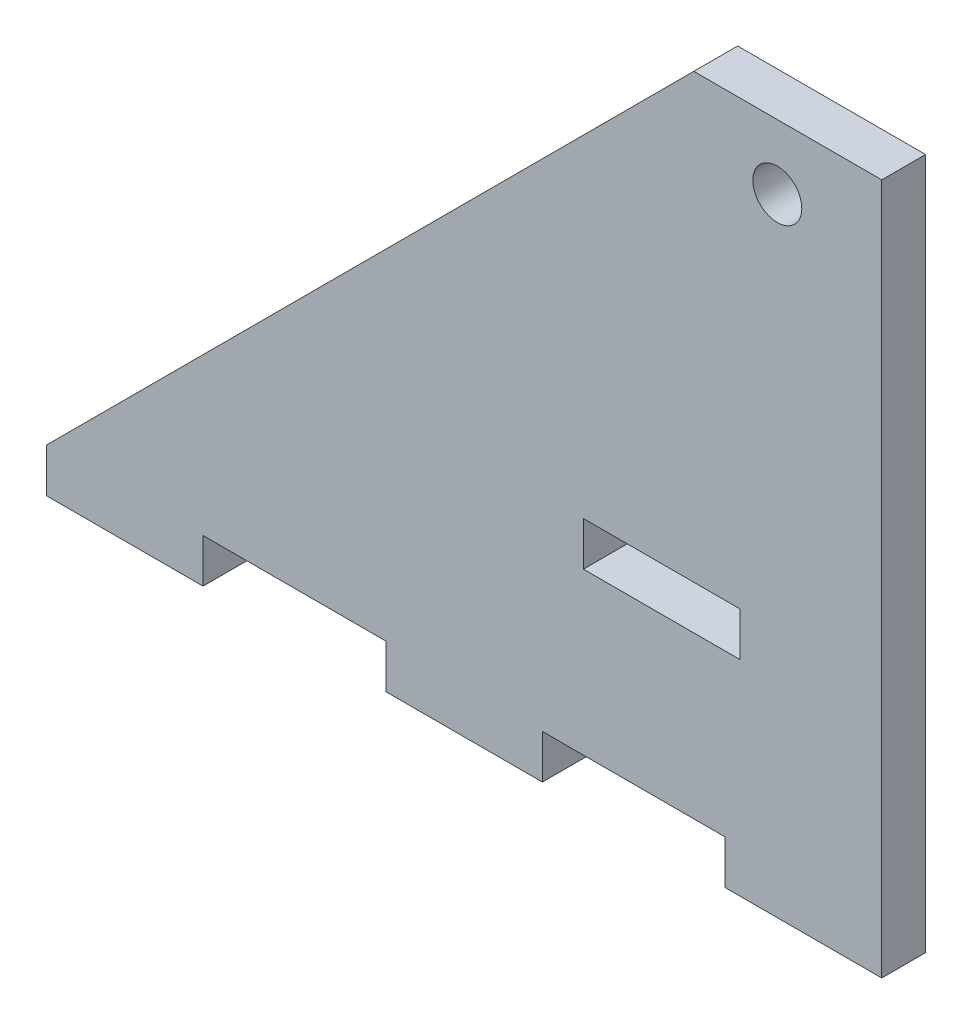
SolidWorks part; units mm, degrees
ref_plane "Front Plane" through (0, 0, 0) normal (0, 0, 1) x (1, 0, 0)
ref_plane "Top Plane" through (0, 0, 0) normal (0, 1, 0) x (1, 0, 0)
ref_plane "Right Plane" through (0, 0, 0) normal (1, 0, 0) x (0, 0, -1)
sketch "Sketch1" plane through (0, 0, 0) normal (0, 0, 1) x (1, 0, 0)
  line L0 (78.74, 78.74) -> (0, 0)
  line L1 (0, 0) -> (101.6, 0)
  line L3 (78.74, 78.74) -> (101.6, 78.74)
  line L4 (101.6, 0) -> (101.6, 78.74)
  dimension "D1" = 101.6
  dimension "D2" = 78.74
  dimension "D3" = 45
extrude "Base" add sketch "Sketch1" along normal blind 5.334
sketch "Sketch2" plane through (0, 0, 5.334) normal (0, 0, 1) x (1, 0, 0)
  line L0 (0, 0) -> (101.6, 0) construction
  line L1 (101.6, 0) -> (101.6, 78.74) construction
  line L2 (74.84, 46.5134) -> (74.84, 24.9234) construction
  line L3 (65.315, 24.9234) -> (84.365, 24.9234)
  line L4 (65.315, 24.9234) -> (65.315, 19.5894)
  line L5 (65.315, 19.5894) -> (84.365, 19.5894)
  line L6 (84.365, 24.9234) -> (84.365, 19.5894)
  line L7 (88.9, 70.866) -> (-24911.1, -43230.4042) construction
  circle A0 centre (88.9, 70.866) radius 2.975
  circle A1 centre (74.84, 46.5134) radius 3 construction
  dimension "D1" = 5.95
  dimension "D4" = 6
  dimension "D2" = 70.866
  dimension "D3" = 12.7
  dimension "D5" = 28.12
  dimension "D6" = 19.05
  dimension "D7" = 5.334
  dimension "D8" = 21.59
  dimension "D9" = 60
extrude "Mount Points" cut sketch "Sketch2" against normal through all
sketch "Sketch3" plane through (0, 0, 0) normal (0, -1, 0) x (1, 0, 0)
  line L0 (0, 5.334) -> (101.6, 5.334) construction
  line L1 (0, 0) -> (19.05, 0)
  line L2 (0, 0) -> (0, 5.334)
  line L3 (0, 5.334) -> (19.05, 5.334)
  line L4 (19.05, 0) -> (19.05, 5.334)
  line L5 (0, 0) -> (101.6, 0) construction
  line L6 (101.6, 0) -> (82.55, 0)
  line L7 (101.6, 0) -> (101.6, 5.334)
  line L8 (101.6, 5.334) -> (82.55, 5.334)
  line L9 (82.55, 0) -> (82.55, 5.334)
  line L10 (41.275, 0) -> (60.325, 0)
  line L11 (41.275, 0) -> (41.275, 5.334)
  line L12 (41.275, 5.334) -> (60.325, 5.334)
  line L13 (60.325, 0) -> (60.325, 5.334)
  line L14 (19.05, 2.667) -> (41.275, 2.667) construction
  line L15 (60.325, 2.667) -> (82.55, 2.667) construction
  dimension "D1" = 19.05
  dimension "D2" = 22.225
extrude "Tabs" add sketch "Sketch3" along normal blind 5.334
equation "\"material\"= \"mdf@base.assembly\""
equation "\"D1@Base\"=\"material\""
equation "\"D7@Sketch2\"=\"mdf@base.assembly\""
equation "\"D1@Tabs\"=\"mdf@base.assembly\""
